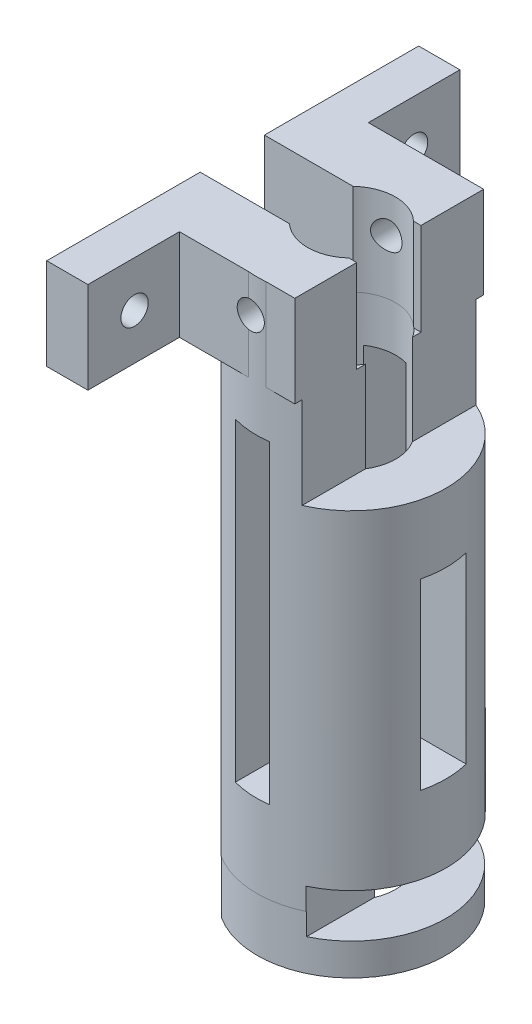
SolidWorks part; units mm, degrees
ref_plane "前基準面" through (0, 0, 0) normal (0, 0, 1) x (1, 0, 0)
ref_plane "上基準面" through (0, 0, 0) normal (0, 1, 0) x (1, 0, 0)
ref_plane "右基準面" through (0, 0, 0) normal (1, 0, 0) x (0, 0, -1)
sketch "草圖1" plane through (0, 0, 0) normal (0, 1, 0) x (1, 0, 0)
  circle A0 centre (0, 0) radius 9.68
  dimension "D1" = 19.36
extrude "伸長-薄件1" add sketch "草圖1" along normal blind 116.68 thin
ref_plane "平面1" through (-21, 0, 0) normal (1, 0, 0) x (0, 0, -1)
sketch "草圖11" plane through (0, 116.68, 0) normal (0, 1, 0) x (1, 0, 0)
  line L0 (-993.1634, -44.2358) -> (49006.8366, -44.2358) construction
  line L2 (35.2085, 30.7642) -> (8.2085, 30.7642)
  line L3 (35.2085, 30.7642) -> (35.2085, -119.2358)
  line L4 (35.2085, -119.2358) -> (8.2085, -119.2358)
  line L5 (8.2085, 30.7642) -> (8.2085, -119.2358)
  line L6 (35.2085, 30.7642) -> (8.2085, -119.2358) construction
  line L7 (35.2085, -119.2358) -> (8.2085, 30.7642) construction
  circle A0 centre (0, 0) radius 20.68 construction
  point P1 (21.7085, -44.2358)
  dimension "D1" = 150
  dimension "D2" = 27
  dimension "D3" = 30.7642
extrude "除料-伸長3" cut sketch "草圖11" against normal blind 40
ref_plane "平面2" through (0, 0, 21) normal (0, 0, 1) x (1, 0, 0)
sketch "草圖13" plane through (0, 0, 21) normal (0, 0, 1) x (1, 0, 0)
  line L0 (-21, -22.649) -> (-21, 22.649) construction
  line L1 (-21, 122.7847) -> (-11, 122.7847)
  line L2 (-21, 122.7847) -> (-21, -5.5603)
  line L3 (-21, -5.5603) -> (-11, -5.5603)
  line L4 (-11, 122.7847) -> (-11, -5.5603)
  dimension "D1" = 10
extrude "除料-伸長7" cut sketch "草圖13" against normal through all
sketch "草圖15" plane through (0, 0, 21) normal (0, 0, 1) x (1, 0, 0)
  line L0 (-1.3957, -883.32) -> (-1.3957, 49116.68) construction
  line L1 (8.2085, 116.68) -> (-11, 116.68) construction
  line L2 (-11, 0) -> (20.68, 0) construction
  line L3 (2.6043, 86.68) -> (-5.3957, 86.68)
  line L4 (2.6043, 86.68) -> (2.6043, 18)
  line L5 (2.6043, 18) -> (-5.3957, 18)
  line L6 (-5.3957, 86.68) -> (-5.3957, 18)
  line L7 (2.6043, 86.68) -> (-5.3957, 18) construction
  line L8 (2.6043, 18) -> (-5.3957, 86.68) construction
  point P1 (-1.3957, 52.34)
  point P5 (-1.3957, 116.68)
  dimension "D1" = 30
  dimension "D2" = 18
  dimension "D3" = 8
extrude "除料-伸長9" cut sketch "草圖15" against normal blind 48
sketch "草圖16" plane through (8.2085, 0, 0) normal (1, 0, 0) x (0, 0, -1)
  line L0 (20.68, 86.68) -> (20.68, 116.68) construction
  line L1 (5.1306, 116.68) -> (20.68, 116.68)
  line L2 (5.1306, 116.68) -> (5.1306, 96.68)
  line L3 (5.1306, 96.68) -> (20.68, 96.68)
  line L4 (20.68, 116.68) -> (20.68, 96.68)
  line L5 (-5.1306, 76.68) -> (-5.1306, 116.68) construction
  line L6 (-5.1306, 96.68) -> (-20.59, 96.68)
  line L7 (-5.1306, 96.68) -> (-5.1306, 116.68)
  line L8 (-5.1306, 116.68) -> (-20.59, 116.68)
  line L9 (-20.59, 96.68) -> (-20.59, 116.68)
  line L10 (-17.5118, 116.68) -> (-20.68, 116.68) construction
  dimension "D1" = 20
extrude "填料-伸長4" add sketch "草圖16" against normal blind 19.2
sketch "草圖17" plane through (0, 116.68, 0) normal (0, 1, 0) x (1, 0, 0)
  line L0 (-1009.59, 0) -> (48990.41, 0) construction
  line L1 (8.2085, 20.68) -> (8.2085, 5.1306) construction
  line L2 (8.2085, 6.97) -> (-11, 6.97)
  line L3 (8.2085, 6.97) -> (8.2085, -7.06)
  line L4 (8.2085, -7.06) -> (-11, -7.06)
  line L5 (-11, 6.97) -> (-11, -7.06)
  line L6 (-11, -17.5118) -> (-11, 17.5118) construction
  line L7 (-10.9915, -20.59) -> (-1.9273, -20.59) construction
  arc A0 (-8.2085, 5.1306) -> (-8.2085, -5.1306) centre (0, 0) ccw construction
  point P6 (-9.68, 0)
  dimension "D1" = 14.03
  dimension "D2" = 13.53
extrude "除料-伸長10" cut sketch "草圖17" against normal blind 20.2
sketch "草圖18" plane through (0, 0, 0) normal (0, -1, 0) x (1, 0, 0)
  circle A0 centre (0, 0) radius 9.59
extrude "除料-伸長11" cut sketch "草圖18" against normal through all
sketch "草圖21" plane through (0, 0, -20.68) normal (0, 0, -1) x (-1, 0, 0)
  line L0 (1.3915, 96.68) -> (1.3915, 105.73) construction
  line L1 (0, 96.68) -> (10.9915, 96.68) construction
  line L2 (1.3915, 105.73) -> (1.3915, 108.73) construction
  circle A0 centre (1.3915, 108.73) radius 2.985
  dimension "D3" = 5.97
  dimension "D1" = 9.05
  dimension "D2" = 3
extrude "除料-伸長12" cut sketch "草圖21" against normal blind 55.2
sketch "草圖23" plane through (0, 0, -20.68) normal (0, 0, -1) x (-1, 0, 0)
  line L0 (1.3915, 105.745) -> (1.3915, -11.785) construction
  circle A0 centre (1.3915, 108.73) radius 2.985 construction
  dimension "D1" = 117.53
sketch "草圖24" plane through (0, 0, 0) normal (0, -1, 0) x (1, 0, 0)
  circle A0 centre (0, 0) radius 9.59
extrude "伸長-薄件2" add sketch "草圖24" along normal blind 55.2 thin
sketch "草圖25" plane through (0, 0, 21) normal (0, 0, 1) x (1, 0, 0)
  line L0 (-1.3915, -11.785) -> (22.6124, -11.785)
  line L1 (22.6124, -11.785) -> (22.6124, -63.8733)
  line L2 (-22.7495, -63.8733) -> (22.6124, -63.8733)
  line L3 (-22.7495, -63.8733) -> (-22.7495, -11.785)
  line L4 (-22.7495, -11.785) -> (-1.3915, -11.785)
extrude "除料-伸長13" cut sketch "草圖25" against normal blind 55.2
sketch "草圖26" plane through (0, 0, 0) normal (0, 1, 0) x (1, 0, 0)
  line L0 (-21, -22.649) -> (-21, 22.649) construction
  line L1 (-10.9915, 20.68) -> (-21, 20.68)
  line L2 (-10.9915, 20.68) -> (-10.9915, -21)
  line L3 (-10.9915, -21) -> (-21, -21)
  line L4 (-21, 20.68) -> (-21, -21)
  line L5 (-17.6, -21) -> (17.6, -21) construction
extrude "除料-伸長15" cut sketch "草圖26" against normal blind 55.2
ref_plane "平面3" through (21, 0, 0) normal (1, 0, 0) x (0, 0, -1)
sketch "草圖27" plane through (21, 0, 0) normal (1, 0, 0) x (0, 0, -1)
  line L0 (0, -923.32) -> (0, 49076.68) construction
  line L1 (5.1306, 76.68) -> (-5.1306, 76.68) construction
  line L2 (18.9811, 76.68) -> (-18.9811, 76.68) construction
  line L3 (-5, 61.68) -> (5, 61.68)
  line L4 (-5, 61.68) -> (-5, 21.68)
  line L5 (-5, 21.68) -> (5, 21.68)
  line L6 (5, 61.68) -> (5, 21.68)
  line L7 (-5, 61.68) -> (5, 21.68) construction
  line L8 (-5, 21.68) -> (5, 61.68) construction
  point P1 (0, 41.68)
  point P5 (0, 76.68)
  dimension "D1" = 15
  dimension "D2" = 40
  dimension "D3" = 10
extrude "除料-伸長16" cut sketch "草圖27" against normal blind 55.2
sketch "草圖28" plane through (21, 0, 0) normal (1, 0, 0) x (0, 0, -1)
  line L1 (-22.4403, 4.804) -> (22.4403, 4.804)
  line L2 (-22.4403, 4.804) -> (-22.4403, -4.804)
  line L3 (-22.4403, -4.804) -> (22.4403, -4.804)
  line L4 (22.4403, 4.804) -> (22.4403, -4.804)
  line L5 (-22.4403, 4.804) -> (22.4403, -4.804) construction
  line L6 (-22.4403, -4.804) -> (22.4403, 4.804) construction
  point P0 (0, 0)
extrude "除料-伸長17" cut sketch "草圖28" against normal blind 12.2
sketch "草圖35" plane through (-10.9915, 0, 0) normal (-1, 0, 0) x (0, 0, 1)
  line L0 (20.59, 116.68) -> (20.59, 96.68)
  line L1 (20.59, 96.68) -> (7.06, 96.68)
  line L2 (7.06, 96.68) -> (7.06, 116.68)
  line L3 (7.06, 116.68) -> (20.59, 116.68)
extrude "填料-伸長10" add sketch "草圖35" along normal blind 15
sketch "草圖36" plane through (-10.9915, 0, 0) normal (-1, 0, 0) x (0, 0, 1)
  line L0 (-20.68, 116.68) -> (-6.97, 116.68)
  line L1 (-6.97, 116.68) -> (-6.97, 96.48)
  line L2 (-6.97, 96.48) -> (-20.68, 96.68)
  line L3 (-20.68, 96.68) -> (-20.68, 116.68)
extrude "填料-伸長11" add sketch "草圖36" along normal blind 15
sketch "草圖37" plane through (0, 0, 20.59) normal (0, 0, 1) x (1, 0, 0)
  line L0 (-25.9915, 96.68) -> (-1.9273, 96.68) construction
  line L1 (-25.9915, 116.68) -> (-16.9915, 116.68)
  line L2 (-25.9915, 116.68) -> (-25.9915, 96.68)
  line L3 (-25.9915, 96.68) -> (-16.9915, 96.68)
  line L4 (-16.9915, 116.68) -> (-16.9915, 96.68)
  dimension "D1" = 9
extrude "填料-伸長12" add sketch "草圖37" along normal blind 20
sketch "草圖38" plane through (0, 0, -20.68) normal (0, 0, -1) x (-1, 0, 0)
  line L0 (25.9915, 116.68) -> (-8.2085, 116.68) construction
  line L1 (25.9915, 96.68) -> (16.9915, 96.68)
  line L2 (25.9915, 96.68) -> (25.9915, 116.68)
  line L3 (25.9915, 116.68) -> (16.9915, 116.68)
  line L4 (16.9915, 96.68) -> (16.9915, 116.68)
  dimension "D1" = 9
extrude "填料-伸長13" add sketch "草圖38" along normal blind 20
sketch "草圖42" plane through (-16.9915, 0, 0) normal (1, 0, 0) x (0, 0, -1)
  line L0 (30.68, -903.32) -> (30.68, 49096.68) construction
  line L1 (40.68, 96.68) -> (20.68, 96.68) construction
  line L2 (-959.32, 106.68) -> (49040.68, 106.68) construction
  line L3 (40.68, 116.68) -> (40.68, 96.68) construction
  line L4 (-30.59, -903.32) -> (-30.59, 49096.68) construction
  line L5 (-40.59, 96.68) -> (-20.59, 96.68) construction
  circle A0 centre (30.68, 106.5544) radius 2.985
  circle A1 centre (-30.3956, 106.68) radius 2.985
  point P5 (30.68, 96.68)
  point P10 (40.68, 106.68)
  point P15 (-30.59, 96.68)
  dimension "D1" = 5.97
  dimension "D2" = 5.97
extrude "除料-伸長21" cut sketch "草圖42" against normal blind 20
